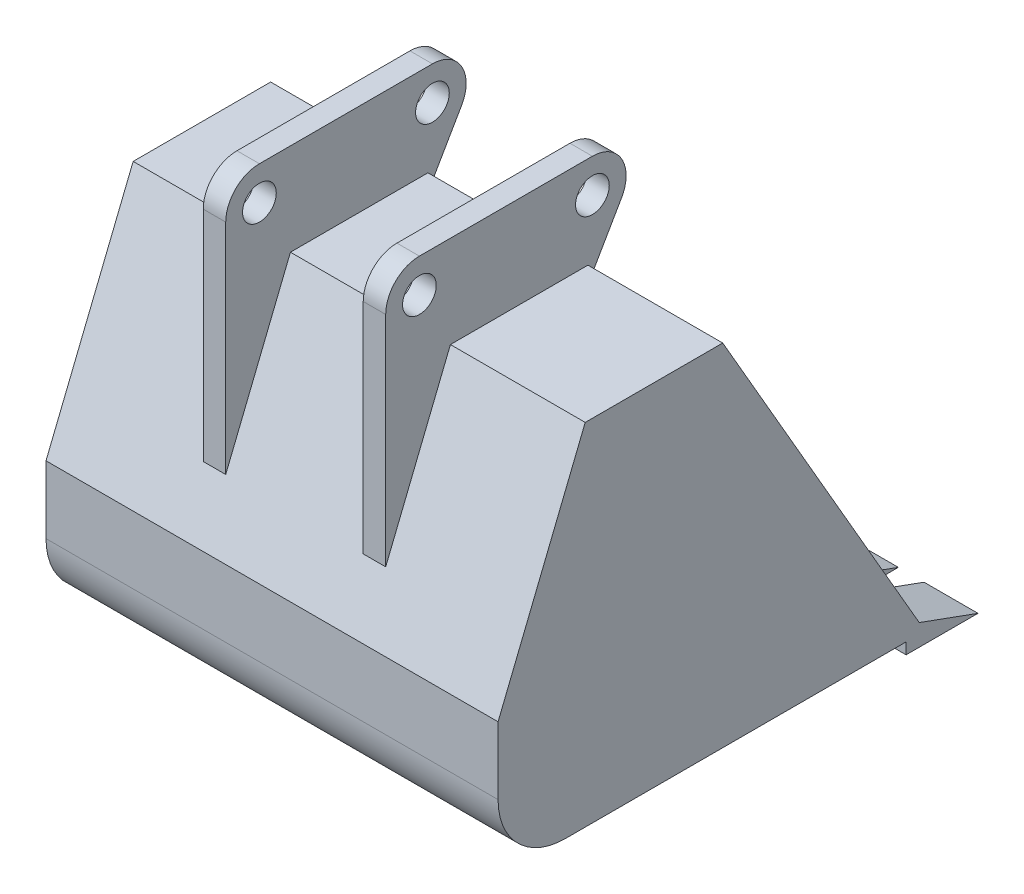
SolidWorks part; units mm, degrees
ref_plane "Front Plane" through (0, 0, 0) normal (0, 0, 1) x (1, 0, 0)
ref_plane "Top Plane" through (0, 0, 0) normal (0, 1, 0) x (1, 0, 0)
ref_plane "Right Plane" through (0, 0, 0) normal (1, 0, 0) x (0, 0, -1)
sketch "Sketch1" plane through (0, 0, 0) normal (1, 0, 0) x (0, 0, -1)
  line L0 (150, 0) -> (908, 0)
  line L2 (499.9326, 780) -> (193.9326, 780)
  line L3 (193.9326, 780) -> (0, 300)
  line L4 (0, 300) -> (0, 150)
  line L5 (908, 0) -> (908, -25)
  line L6 (908, -25) -> (1068, -25)
  line L7 (1068, -25) -> (937.217, 22.6011)
  line L8 (937.217, 22.6011) -> (499.9326, 780)
  line L9 (49.9326, 668.2098) -> (49.9326, 910) construction
  line L10 (124.9326, 985) -> (509.9326, 985) construction
  line L11 (574.8845, 872.5) -> (510.7061, 761.3397) construction
  line L12 (124.9326, 910) -> (509.9326, 910) construction
  line L13 (937.217, 22.6011) -> (919.8917, -25) construction
  arc A0 (150, 0) -> (0, 150) centre (150, 150) cw
  circle A1 centre (509.9326, 910) radius 29.5678 construction
  circle A2 centre (124.9326, 910) radius 35.2851 construction
  arc A3 (49.9326, 910) -> (124.9326, 985) centre (124.9326, 910) cw construction
  arc A4 (509.9326, 985) -> (574.8845, 872.5) centre (509.9326, 910) cw construction
  point P8 (0, 0)
  point P9 (917.7957, -25)
  point P24 (0, 300)
  point P25 (193.7873, 780)
  point P26 (158.0494, 780)
  dimension "D3" = 150
  dimension "D14" = 75
  dimension "D1" = 306
  dimension "D2" = 780
  dimension "D4" = 150
  dimension "D5" = 758
  dimension "D6" = 25
  dimension "D7" = 20
  dimension "D8" = 60
  dimension "D9" = 1068
  dimension "D10" = 144
  dimension "D11" = 1010
  dimension "D12" = 120
  dimension "D13" = 385
  dimension "D15" = 112
extrude "Boss-Extrude1" add sketch "Sketch1" along normal mid plane 1006
sketch "Sketch2" plane through (0, 0, 0) normal (1, 0, 0) x (0, 0, -1)
  line L13 (908, 40) -> (1011.7133, 40)
  line L14 (1011.7133, 40) -> (1011.7133, 740)
  line L15 (1011.7133, 740) -> (499.9326, 740)
  line L17 (150, 40) -> (908, 40)
  line L18 (40, 292.2248) -> (40, 150)
  line L19 (220.9129, 740) -> (40, 292.2248)
  line L20 (499.9326, 740) -> (220.9129, 740)
  line L21 (150, 40) -> (908, 40)
  line L22 (40, 292.2248) -> (40, 150)
  line L23 (220.9129, 740) -> (40, 292.2248)
  line L24 (499.9326, 740) -> (220.9129, 740)
  arc A3 (40, 150) -> (150, 40) centre (150, 150) ccw
  arc A4 (40, 150) -> (150, 40) centre (150, 150) ccw
  dimension "D1" = 40
extrude "Cut-Extrude1" cut sketch "Sketch2" against normal mid plane 926
sketch "Sketch3" plane through (0, 0, 0) normal (1, 0, 0) x (0, 0, -1)
  line L0 (946.7966, 48.9207) -> (905.0797, -65.6954)
  line L1 (905.0797, -65.6954) -> (1089.9448, -65.6954)
  line L2 (1089.9448, -65.6954) -> (1089.9448, 48.9207)
  line L3 (1089.9448, 48.9207) -> (946.7966, 48.9207)
  line L4 (1068, -25) -> (937.217, 22.6011) construction
  dimension "D1" = 90
extrude "Cut-Extrude2" cut sketch "Sketch3" against normal mid plane 57.2
pattern_linear "LPattern1" count 3 spacing 177.2 along (1, 0, 0) count 3 spacing 177.2 along (-1, 0, 0) of "Cut-Extrude2"
ref_plane "Plane1" through (153, 0, 0) normal (1, 0, 0) x (0, 0, -1)
sketch "Sketch5" plane through (153, 0, 0) normal (1, 0, 0) x (0, 0, -1)
  line L0 (49.9326, 423.5875) -> (49.9326, 910)
  line L1 (193.9326, 780) -> (0, 300) construction
  line L2 (124.9326, 985) -> (509.9326, 985)
  line L3 (510.7061, 761.3397) -> (574.8845, 872.5)
  line L4 (937.217, 22.6011) -> (499.9326, 780) construction
  line L5 (908, -25) -> (1068, -25) construction
  line L6 (124.9326, 910) -> (509.9326, 910) construction
  line L9 (499.9326, 780) -> (193.9326, 780) construction
  line L10 (499.9326, 780) -> (193.9326, 780)
  line L11 (193.9326, 780) -> (49.9326, 423.5875)
  line L12 (499.9326, 780) -> (510.7061, 761.3397)
  circle A0 centre (124.9326, 910) radius 37.5
  circle A1 centre (509.9326, 910) radius 37.5
  arc A2 (574.8845, 872.5) -> (509.9326, 985) centre (509.9326, 910) ccw
  arc A3 (49.9326, 910) -> (124.9326, 985) centre (124.9326, 910) cw
  dimension "D1" = 75
  dimension "D2" = 75
  dimension "D3" = 1010
  dimension "D4" = 385
  dimension "D5" = 120
  dimension "D6" = 144
extrude "Boss-Extrude2" add sketch "Sketch5" along normal blind 50
mirror "Mirror1" about plane through (0, 0, 0) normal (1, 0, 0) of "Boss-Extrude2"
